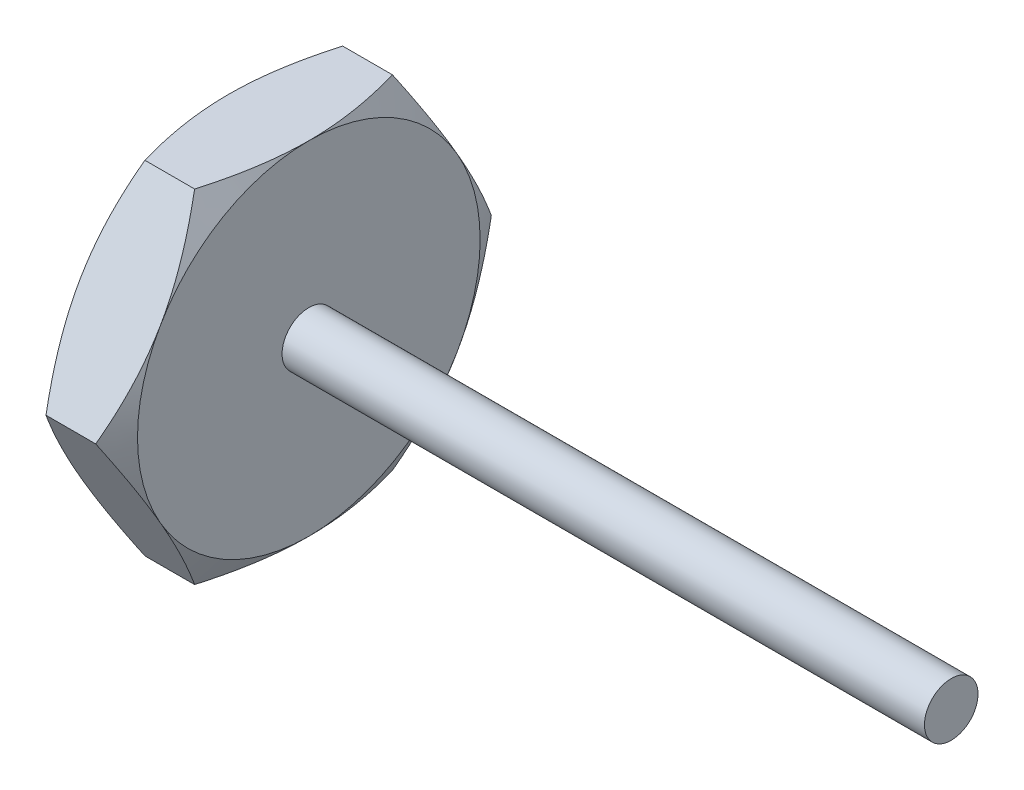
SolidWorks part; units mm, degrees
ref_plane "Ön Düzlem" through (0, 0, 0) normal (0, 0, 1) x (1, 0, 0)
ref_plane "Üst Düzlem" through (0, 0, 0) normal (0, 1, 0) x (1, 0, 0)
ref_plane "Sağ Düzlem" through (0, 0, 0) normal (1, 0, 0) x (0, 0, -1)
sketch "Çizim1" plane through (0, 0, 0) normal (1, 0, 0) x (0, 0, -1)
  line L1 (-6.2253, 7.8654) -> (-10.8441, 15.8654)
  line L2 (-10.8441, 15.8654) -> (-20.0817, 15.8654)
  line L3 (-20.0817, 15.8654) -> (-24.7006, 7.8654)
  line L4 (-24.7006, 7.8654) -> (-20.0817, -0.1346)
  line L5 (-20.0817, -0.1346) -> (-10.8441, -0.1346)
  line L6 (-10.8441, -0.1346) -> (-6.2253, 7.8654)
  circle A0 centre (-15.4629, 7.8654) radius 8 construction
  dimension "D1" = 16
extrude "Yükseklik-Ekstrüzyon1" add sketch "Çizim1" along normal blind 3.75
sketch "Çizim2" plane through (3.75, 0, 0) normal (1, 0, 0) x (0, 0, -1)
  circle A0 centre (-15.4629, 7.8654) radius 1.25
  dimension "D1" = 2.5
extrude "Yükseklik-Ekstrüzyon2" add sketch "Çizim2" along normal blind 30
sketch "Çizim3" plane through (0, 0, 0) normal (-1, 0, 0) x (0, 0, 1)
  circle A0 centre (15.4629, 7.8654) radius 8
extrude "Kes-Ekstrüzyon1" cut sketch "Çizim3" against normal blind 10 draft 60 flip side to cut
sketch "Çizim4" plane through (3.75, 0, 0) normal (1, 0, 0) x (0, 0, -1)
  circle A0 centre (-15.4629, 7.8654) radius 8
extrude "Kes-Ekstrüzyon2" cut sketch "Çizim4" against normal blind 10 draft 60 flip side to cut
